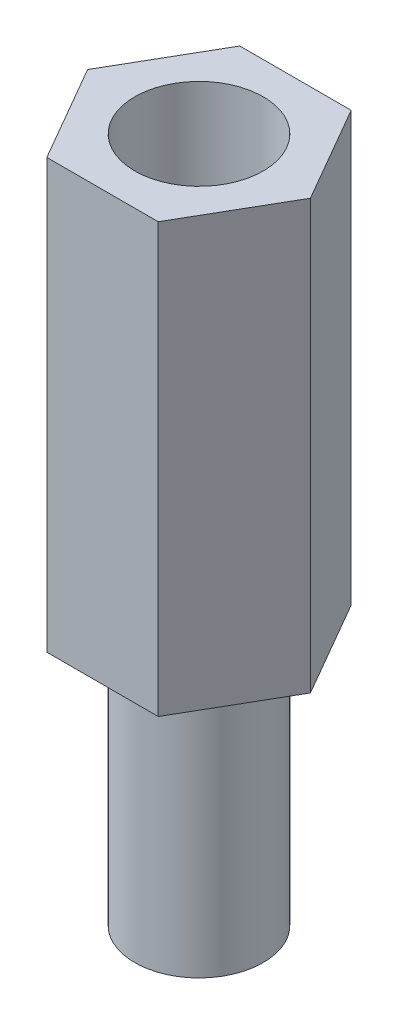
SolidWorks part; units mm, degrees
material "尼龙 101"
ref_plane "前视基准面" through (0, 0, 0) normal (0, 0, 1) x (1, 0, 0)
ref_plane "上视基准面" through (0, 0, 0) normal (0, 1, 0) x (1, 0, 0)
ref_plane "右视基准面" through (0, 0, 0) normal (1, 0, 0) x (0, 0, -1)
other "Configuration Table"
sketch "草图1" plane through (0, 0, 0) normal (0, 1, 0) x (1, 0, 0)
  line L1 (2.6, 0) -> (1.3, 2.2517)
  line L2 (1.3, 2.2517) -> (-1.3, 2.2517)
  line L3 (-1.3, 2.2517) -> (-2.6, 0)
  line L4 (-2.6, 0) -> (-1.3, -2.2517)
  line L5 (-1.3, -2.2517) -> (1.3, -2.2517)
  line L6 (1.3, -2.2517) -> (2.6, 0)
  circle A0 centre (0, 0) radius 2.6 construction
  dimension "D1" = 5.2
extrude "凸台-拉伸2" add sketch "草图1" along normal blind 10
sketch "草图2" plane through (0, 10, 0) normal (0, 1, 0) x (1, 0, 0)
  circle A0 centre (0, 0) radius 1.5
extrude "切除-拉伸1" cut sketch "草图2" against normal blind 7
sketch "草图3" plane through (0, 0, 0) normal (0, -1, 0) x (1, 0, 0)
  circle A0 centre (0, 0) radius 1.5
extrude "凸台-拉伸3" add sketch "草图3" along normal blind 6
